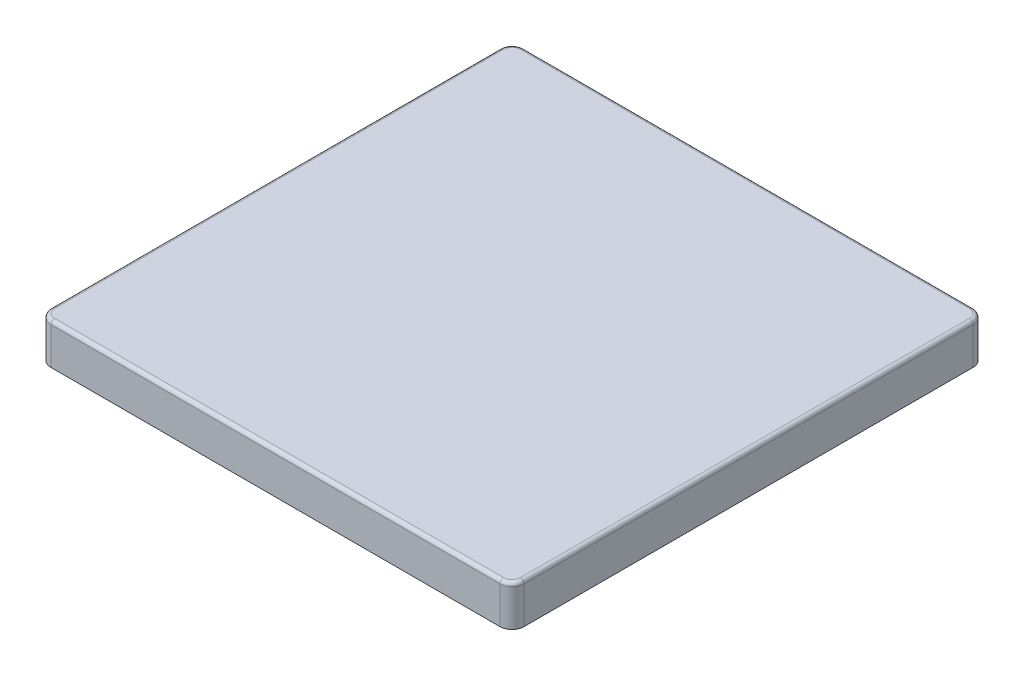
SolidWorks part; units mm, degrees
ref_plane "Front Plane" through (0, 0, 0) normal (0, 0, 1) x (1, 0, 0)
ref_plane "Top Plane" through (0, 0, 0) normal (0, 1, 0) x (1, 0, 0)
ref_plane "Right Plane" through (0, 0, 0) normal (1, 0, 0) x (0, 0, -1)
sketch "Sketch1" plane through (0, 0, 0) normal (0, 1, 0) x (1, 0, 0)
  line L1 (0, 0) -> (100, 0)
  line L2 (0, 0) -> (0, 100)
  line L3 (0, 100) -> (100, 100)
  line L4 (100, 0) -> (100, 100)
  dimension "D1" = 100
  dimension "D2" = 100
extrude "Boss-Extrude1" add sketch "Sketch1" along normal blind 8.6
fillet "Fillet1" radius 2.54 4 edges at (100, 4.3, 0) (100, 4.3, -100) (0, 4.3, -100) (0, 4.3, 0)
fillet "Fillet2" radius 0.762 8 edges at (99.2561, 8.6, -0.7439) (50, 8.6, 0) (0.7439, 8.6, -0.7439) (0, 8.6, -50) (0.7439, 8.6, -99.2561) (50, 8.6, -100) (99.2561, 8.6, -99.2561) (100, 8.6, -50)
